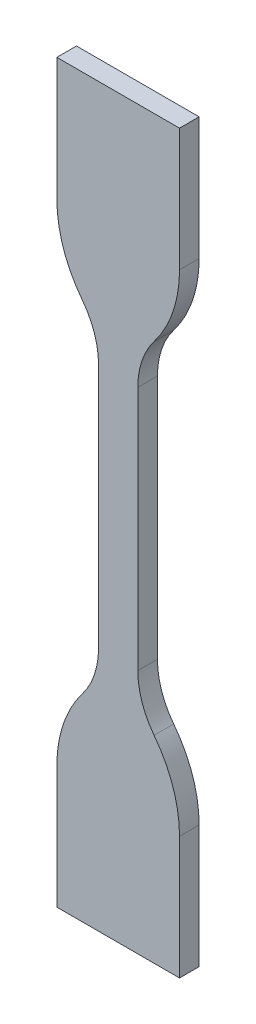
SolidWorks part; units mm, degrees
ref_plane "Front Plane" through (0, 0, 0) normal (0, 0, 1) x (1, 0, 0)
ref_plane "Top Plane" through (0, 0, 0) normal (0, 1, 0) x (1, 0, 0)
ref_plane "Right Plane" through (0, 0, 0) normal (1, 0, 0) x (0, 0, -1)
sketch "Sketch1" plane through (0, 0, 0) normal (0, 0, 1) x (1, 0, 0)
  line L0 (2, 0) -> (0, 0) construction
  line L1 (2, -12.5) -> (2, 12.5)
  line L2 (6.25, 19.5666) -> (6.25, 37.5)
  line L3 (0, 0) -> (0, 37.5) construction
  line L4 (6.25, 37.5) -> (-6.25, 37.5)
  line L5 (-2, -12.5) -> (-2, 12.5)
  line L6 (-6.25, 19.5666) -> (-6.25, 37.5)
  line L7 (6.25, -19.5666) -> (6.25, -37.5)
  line L8 (6.25, -37.5) -> (-6.25, -37.5)
  line L9 (-6.25, -19.5666) -> (-6.25, -37.5)
  arc A0 (2, 12.5) -> (6.25, 19.5666) centre (10, 12.5) cw
  arc A1 (-2, 12.5) -> (-6.25, 19.5666) centre (-10, 12.5) ccw
  arc A2 (2, -12.5) -> (6.25, -19.5666) centre (10, -12.5) ccw
  arc A3 (-2, -12.5) -> (-6.25, -19.5666) centre (-10, -12.5) cw
  point P28 (-2, 0)
  dimension "D2" = 8
  dimension "D1" = 12.5
  dimension "D4" = 25
  dimension "D5" = 4
  dimension "D3" = 75
extrude "Strekkprøve" add sketch "Sketch1" along normal mid plane 2
fillet "Fillet1" radius 12.5 4 edges at (-6.25, -19.5666, 0) (6.25, -19.5666, 0) (-6.25, 19.5666, 0) (6.25, 19.5666, 0)
equation "\"lengde\"= 75'rad"
equation "\"radius\" = 8"
equation "\"tykkelse\" = 2"
equation "\"bredde grep\" = 12.5"
equation "\"bredde tynn\"= 4"
equation "\"lengde strekk\"= 25"
equation "\"D2@Sketch1\"=\"radius\""
equation "\"D1@Sketch1\"=\"bredde grep\""
equation "\"D4@Sketch1\"=\"lengde strekk\""
equation "\"D5@Sketch1\"=\"bredde tynn\""
equation "\"D3@Sketch1\"=\"lengde\""
equation "\"D1@Strekkprøve\" = \"tykkelse\""
